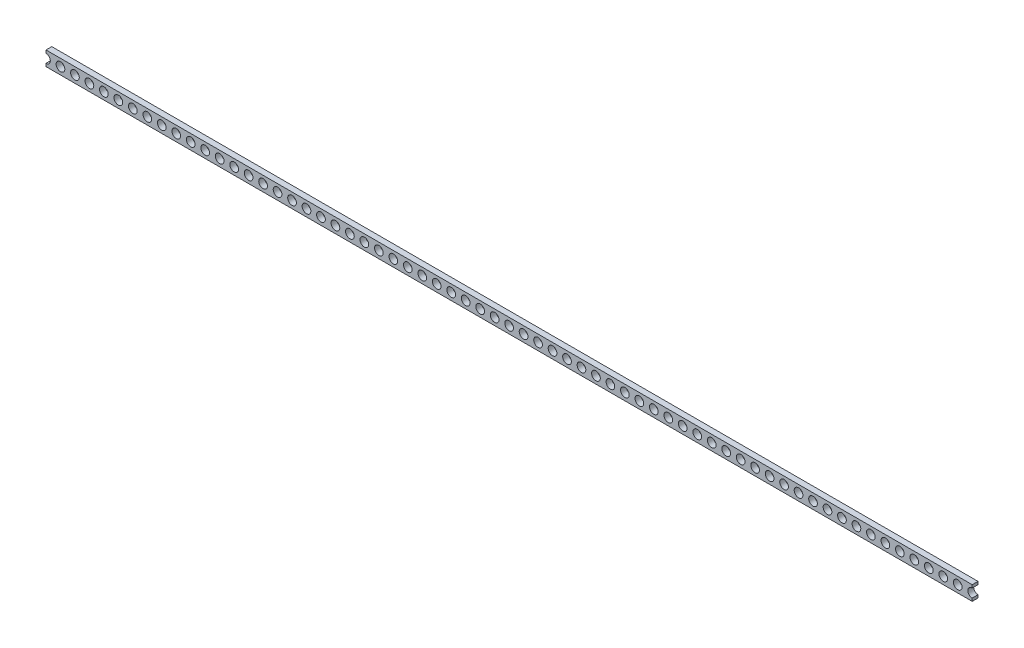
SolidWorks part; units mm, degrees
ref_plane "前视基准面" through (0, 0, 0) normal (0, 0, 1) x (1, 0, 0)
ref_plane "上视基准面" through (0, 0, 0) normal (0, 1, 0) x (1, 0, 0)
ref_plane "右视基准面" through (0, 0, 0) normal (1, 0, 0) x (0, 0, -1)
sketch "草图1" plane through (0, 0, 0) normal (0, 0, 1) x (1, 0, 0)
  line L1 (0, 0) -> (320, 0)
  line L2 (0, 0) -> (0, -5)
  line L3 (0, -5) -> (320, -5)
  line L4 (320, 0) -> (320, -5)
  dimension "D1" = 5
  dimension "D2" = 320
extrude "凸台-拉伸1" add sketch "草图1" along normal blind 2
sketch "草图2" plane through (0, 0, 2) normal (0, 0, 1) x (1, 0, 0)
  line L0 (320, 0) -> (0, 0) construction
  line L1 (160, 0) -> (160, -5) construction
  line L2 (0, -5) -> (320, -5) construction
  circle A0 centre (160, -2.5) radius 1.5
  dimension "D1" = 3
extrude "切除-拉伸1" cut sketch "草图2" against normal through all
pattern_linear "阵列(线性)1" count 35 spacing 5 along (1, 0, 0) of "切除-拉伸1"
pattern_linear "阵列(线性)2" count 35 spacing 5 along (-1, 0, 0) of "切除-拉伸1"
